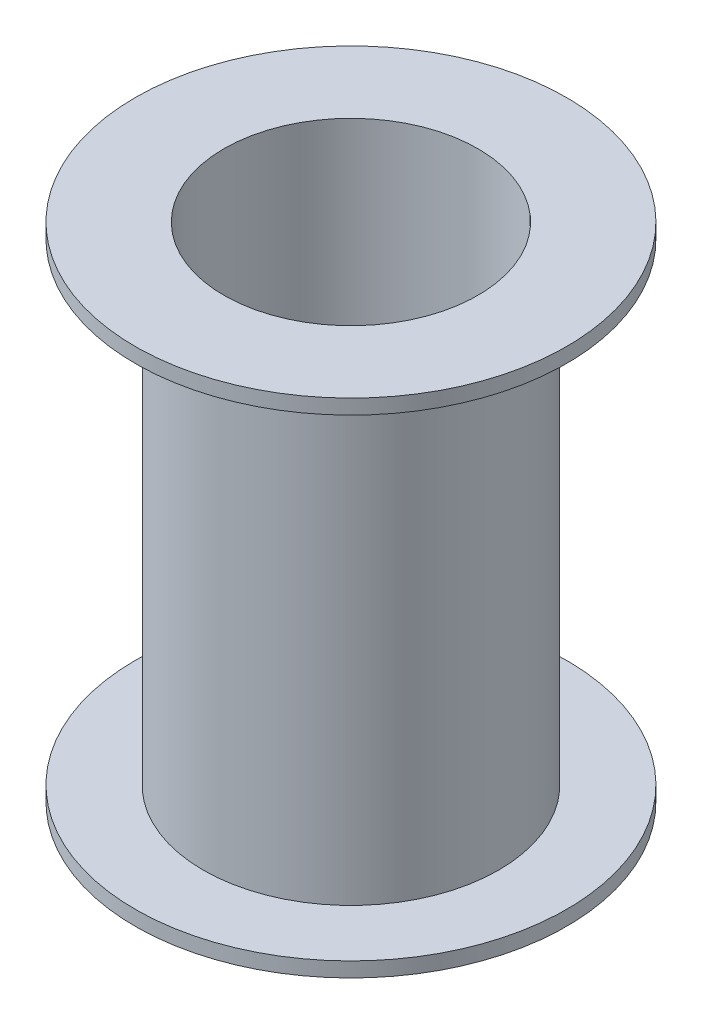
SolidWorks part; units mm, degrees
ref_plane "Front Plane" through (0, 0, 0) normal (0, 0, 1) x (1, 0, 0)
ref_plane "Top Plane" through (0, 0, 0) normal (0, 1, 0) x (1, 0, 0)
ref_plane "Right Plane" through (0, 0, 0) normal (1, 0, 0) x (0, 0, -1)
sketch "Sketch1" plane through (0, 0, 0) normal (0, 0, 1) x (1, 0, 0)
  line L0 (0.43, 0) -> (0.73, 0)
  line L1 (0.73, 0) -> (0.73, 0.05)
  line L2 (0.73, 0.05) -> (0.5, 0.05)
  line L3 (0.5, 0.05) -> (0.5, 1.65)
  line L4 (0.5, 1.65) -> (0.73, 1.65)
  line L5 (0.73, 1.65) -> (0.73, 1.7)
  line L6 (0.73, 1.7) -> (0.43, 1.7)
  line L7 (0, 1.7) -> (0, 0) construction
  line L8 (0.73, 1.65) -> (0.73, 0.05) construction
  line L9 (0.43, 1.7) -> (0.43, 0)
  line L10 (0, 0) -> (0.43, 0) construction
  line L11 (0, 1.7) -> (0.43, 1.7) construction
  dimension "D1" = 0.5
  dimension "D2" = 0.05
  dimension "D3" = 0.05
  dimension "D4" = 1.6
  dimension "D5" = 0.07
  dimension "D6" = 0.3
revolve "Revolve1" add sketch "Sketch1" angle 360 about L7
